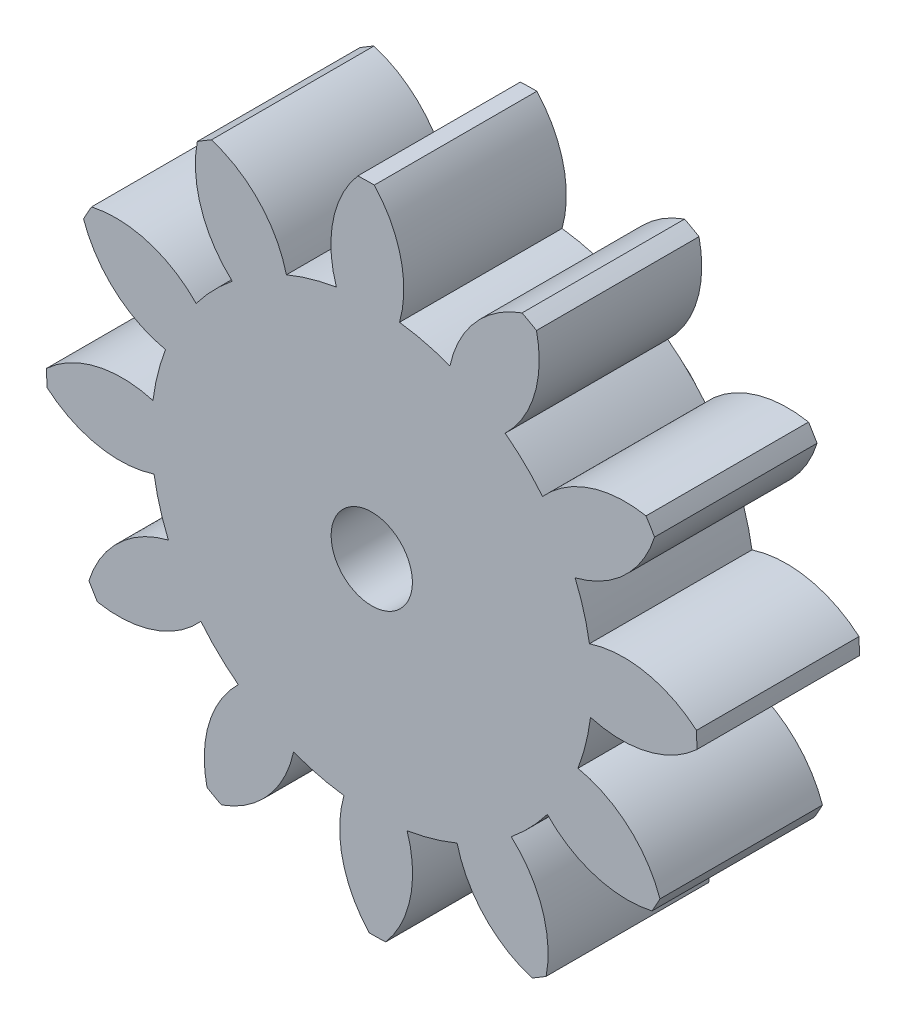
SolidWorks part; units mm, degrees
ref_plane "Front Plane" through (0, 0, 0) normal (0, 0, 1) x (1, 0, 0)
ref_plane "Top Plane" through (0, 0, 0) normal (0, 1, 0) x (1, 0, 0)
ref_plane "Right Plane" through (0, 0, 0) normal (1, 0, 0) x (0, 0, -1)
sketch "Sketch1" plane through (0, 0, 0) normal (0, 0, 1) x (1, 0, 0)
  arc A0 (-10.64, 5.5495) -> (-7.6139, 2.8867) centre (-6.7574, 6.911) ccw
  arc A1 (-7.6139, 2.8867) -> (-8.0779, 1.0257) centre (0, 0) ccw
  arc A2 (-8.0779, 1.0257) -> (-11.9999, 0.0953) centre (-9.211, -2.9296) ccw
  arc A3 (-11.9999, 0.0953) -> (-11.9893, -0.514) centre (0, 0) ccw
  arc A4 (-11.9893, -0.514) -> (-8.0371, -1.307) centre (-9.3076, 2.6064) ccw
  arc A5 (-8.0371, -1.307) -> (-7.5085, -3.1507) centre (0, 0) ccw
  arc A6 (-7.5085, -3.1507) -> (-10.4399, -5.9174) centre (-6.5121, -7.1426) ccw
  arc A7 (-10.4399, -5.9174) -> (-10.126, -6.4398) centre (0, 0) ccw
  arc A8 (-10.126, -6.4398) -> (-6.3069, -5.1504) centre (-9.3638, -2.3966) ccw
  arc A9 (-6.3069, -5.1504) -> (-4.9272, -6.4828) centre (0, 0) ccw
  arc A10 (-4.9272, -6.4828) -> (-6.0825, -10.3446) centre (-2.0684, -9.4417) ccw
  arc A11 (-6.0825, -10.3446) -> (-5.5495, -10.64) centre (0, 0) ccw
  arc A12 (-5.5495, -10.64) -> (-2.8867, -7.6139) centre (-6.911, -6.7574) ccw
  arc A13 (-2.8867, -7.6139) -> (-1.0257, -8.0779) centre (0, 0) ccw
  arc A14 (-1.0257, -8.0779) -> (-0.0953, -11.9999) centre (2.9296, -9.211) ccw
  arc A15 (-0.0953, -11.9999) -> (0.514, -11.9893) centre (0, 0) ccw
  arc A16 (0.514, -11.9893) -> (1.307, -8.0371) centre (-2.6064, -9.3076) ccw
  arc A17 (1.307, -8.0371) -> (3.1507, -7.5085) centre (0, 0) ccw
  arc A18 (3.1507, -7.5085) -> (5.9174, -10.4399) centre (7.1426, -6.5121) ccw
  arc A19 (5.9174, -10.4399) -> (6.4398, -10.126) centre (0, 0) ccw
  arc A20 (6.4398, -10.126) -> (5.1504, -6.3069) centre (2.3966, -9.3638) ccw
  arc A21 (5.1504, -6.3069) -> (6.4828, -4.9272) centre (0, 0) ccw
  arc A22 (6.4828, -4.9272) -> (10.3446, -6.0825) centre (9.4417, -2.0684) ccw
  arc A23 (10.3446, -6.0825) -> (10.64, -5.5495) centre (0, 0) ccw
  arc A24 (10.64, -5.5495) -> (7.6139, -2.8867) centre (6.7574, -6.911) ccw
  arc A25 (7.6139, -2.8867) -> (8.0779, -1.0257) centre (0, 0) ccw
  arc A26 (8.0779, -1.0257) -> (11.9999, -0.0953) centre (9.211, 2.9296) ccw
  arc A27 (11.9999, -0.0953) -> (11.9893, 0.514) centre (0, 0) ccw
  arc A28 (11.9893, 0.514) -> (8.0371, 1.307) centre (9.3076, -2.6064) ccw
  arc A29 (8.0371, 1.307) -> (7.5085, 3.1507) centre (0, 0) ccw
  arc A30 (7.5085, 3.1507) -> (10.4399, 5.9174) centre (6.5121, 7.1426) ccw
  arc A31 (10.4399, 5.9174) -> (10.126, 6.4398) centre (0, 0) ccw
  arc A32 (10.126, 6.4398) -> (6.3069, 5.1504) centre (9.3638, 2.3966) ccw
  arc A33 (6.3069, 5.1504) -> (4.9272, 6.4828) centre (0, 0) ccw
  arc A34 (4.9272, 6.4828) -> (6.0825, 10.3446) centre (2.0684, 9.4417) ccw
  arc A35 (6.0825, 10.3446) -> (5.5495, 10.64) centre (0, 0) ccw
  arc A36 (5.5495, 10.64) -> (2.8867, 7.6139) centre (6.911, 6.7574) ccw
  arc A37 (2.8867, 7.6139) -> (1.0257, 8.0779) centre (0, 0) ccw
  arc A38 (1.0257, 8.0779) -> (0.0953, 11.9999) centre (-2.9296, 9.211) ccw
  arc A39 (0.0953, 11.9999) -> (-0.514, 11.9893) centre (0, 0) ccw
  arc A40 (-0.514, 11.9893) -> (-1.307, 8.0371) centre (2.6064, 9.3076) ccw
  arc A41 (-1.307, 8.0371) -> (-3.1507, 7.5085) centre (0, 0) ccw
  arc A42 (-3.1507, 7.5085) -> (-5.9174, 10.4399) centre (-7.1426, 6.5121) ccw
  arc A43 (-5.9174, 10.4399) -> (-6.4398, 10.126) centre (0, 0) ccw
  arc A44 (-6.4398, 10.126) -> (-5.1504, 6.3069) centre (-2.3966, 9.3638) ccw
  arc A45 (-5.1504, 6.3069) -> (-6.4828, 4.9272) centre (0, 0) ccw
  arc A46 (-6.4828, 4.9272) -> (-10.3446, 6.0825) centre (-9.4417, 2.0684) ccw
  arc A47 (-10.3446, 6.0825) -> (-10.64, 5.5495) centre (0, 0) ccw
extrude "Boss-Extrude1" add sketch "Sketch1" along normal blind 6
sketch "Sketch3" plane through (0, 0, 0) normal (0, 0, -1) x (-1, 0, 0)
  circle A0 centre (0, 0) radius 1.5
  dimension "D1" = 3
extrude "Cut-Extrude1" cut sketch "Sketch3" against normal through all
sketch "Sketch4" plane through (0, 0, 0) normal (0, 0, -1) x (-1, 0, 0)
  circle A0 centre (0, 0) radius 2.5
  circle A1 centre (0, 0) radius 2.25
  dimension "D1" = 5
  dimension "D2" = 4.5
extrude "Boss-Extrude2" add sketch "Sketch4" along normal blind 4 separate body
